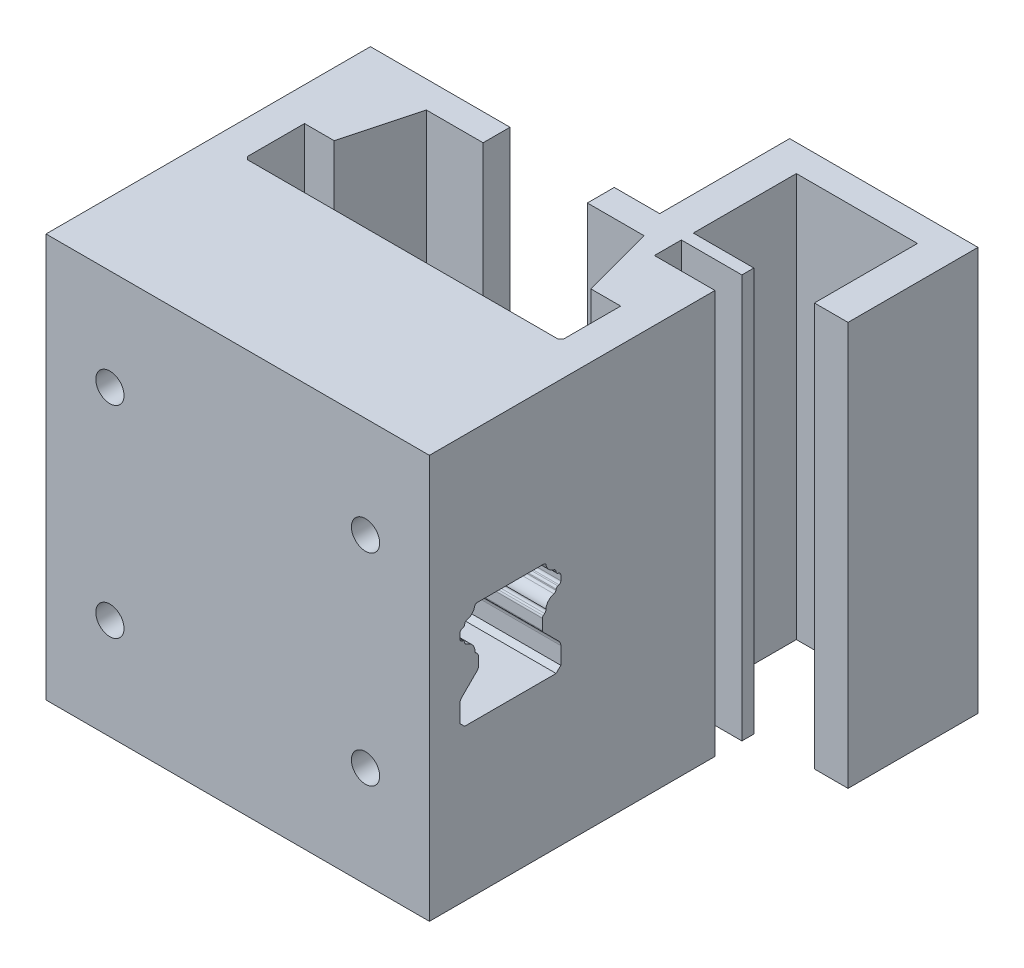
SolidWorks part; units mm, degrees
ref_plane "Front Plane" through (0, 0, 0) normal (0, 0, 1) x (1, 0, 0)
ref_plane "Top Plane" through (0, 0, 0) normal (0, 1, 0) x (1, 0, 0)
ref_plane "Right Plane" through (0, 0, 0) normal (1, 0, 0) x (0, 0, -1)
sketch "Sketch1" plane through (0, 0, 0) normal (0, 1, 0) x (1, 0, 0)
  line L0 (23.07, -9.85) -> (-23.07, -9.85)
  line L1 (-23.5, -9.42) -> (-23.07, -9.85)
  line L2 (-23.5, -9.42) -> (-23.5, -0.95)
  line L7 (-19.0939, -0.95) -> (-23.5, -0.95)
  line L8 (-19.0939, -0.95) -> (-19, -0.5997)
  line L9 (-16.2, 9.85) -> (-19, -0.5997)
  line L10 (16.2, 9.85) -> (-16.2, 9.85)
  line L11 (23.07, -9.85) -> (23.5, -9.42)
  line L12 (23.5, -2.9) -> (23.5, -9.42)
  line L13 (23.5, -2.9) -> (23.5, -0.95)
  line L15 (19.0939, -0.95) -> (23.5, -0.95)
  line L16 (19.0939, -0.95) -> (19, -0.5997)
  line L17 (16.2, 9.85) -> (19, -0.5997)
  line L18 (-28.5, -14.85) -> (28.5, -14.85)
  line L19 (-28.5, -14.85) -> (-28.5, 13.85)
  line L20 (-28.5, 13.85) -> (28.5, 13.85)
  line L21 (28.5, -14.85) -> (28.5, 13.85)
  dimension "D1" = 5
  dimension "D2" = 5
  dimension "D3" = 5
  dimension "D4" = 4
extrude "Boss-Extrude1" add sketch "Sketch1" along normal blind 60
sketch "Sketch2" plane through (0, 0, 0) normal (0, -1, 0) x (1, 0, 0)
  line L0 (0, -25.3794) -> (0, 27.4746) construction
  line L1 (28.5, -8.0706) -> (19.5, -8.0706)
  line L2 (28.5, -8.0706) -> (28.5, -12.0706)
  line L3 (28.5, -12.0706) -> (19.5, -12.0706)
  line L4 (19.5, -8.0706) -> (19.5, -12.0706)
  line L5 (-19.5, -8.0706) -> (-19.5, -12.0706)
  line L6 (-28.5, -12.0706) -> (-19.5, -12.0706)
  line L7 (-28.5, -8.0706) -> (-28.5, -12.0706)
  line L8 (-28.5, -8.0706) -> (-19.5, -8.0706)
  dimension "D1" = 9
  dimension "D2" = 4
extrude "Cut-Extrude1" cut sketch "Sketch2" against normal through all
sketch "Sketch5" plane through (0, 0, 0) normal (1, 0, 0) x (0, 0, -1)
  line L0 (-14.85, 23.2) -> (-14.85, 34.0815)
  line L1 (-15.55, 22.5) -> (-14.85, 23.2)
  line L2 (-29.15, 22.5) -> (-15.55, 22.5)
  line L3 (-29.85, 23.2) -> (-29.15, 22.5)
  line L4 (-29.85, 25.7434) -> (-29.85, 23.2)
  line L5 (-27.2372, 28.7704) -> (-29.5571, 26.4505)
  line L6 (-27.12, 30.6153) -> (-27.12, 29.0533)
  line L7 (-27.4316, 31.0926) -> (-27.2372, 30.8982)
  line L8 (-29.1562, 33.3541) -> (-29.1243, 33.2128)
  line L9 (-29.5857, 33.7052) -> (-29.4106, 33.6421)
  line L10 (-29.85, 34.8375) -> (-29.85, 34.0815)
  line L11 (-29.4277, 35.2633) -> (-29.5687, 35.2195)
  line L12 (-29.125, 35.7021) -> (-29.1553, 35.5612)
  line L13 (-27.399, 37.5) -> (-27.4361, 37.4629)
  line L14 (-17.301, 37.5) -> (-27.399, 37.5)
  line L15 (-17.2639, 37.4629) -> (-17.301, 37.5)
  line L16 (-15.5447, 35.5612) -> (-15.575, 35.7021)
  line L17 (-15.1313, 35.2195) -> (-15.2723, 35.2633)
  line L18 (-14.85, 34.0815) -> (-14.85, 60)
  line L19 (-15.2894, 33.6421) -> (-15.1143, 33.7052)
  line L20 (-15.5757, 33.2128) -> (-15.5438, 33.3541)
  line L21 (-17.4628, 30.8982) -> (-17.2684, 31.0926)
  line L22 (-17.58, 29.0533) -> (-17.58, 30.6153)
  line L23 (-15.1429, 26.4505) -> (-17.4628, 28.7704)
  line L24 (-14.85, 60) -> (-34.3805, 60)
  line L25 (-14.85, 30) -> (-29.85, 30) construction
  line L26 (-34.3805, 60) -> (-34.3805, 0)
  line L27 (-14.85, 34.0815) -> (-14.85, 30) construction
  line L28 (-34.3805, 0) -> (-14.85, 0)
  line L29 (-14.85, 0) -> (-14.85, 23.2)
  arc A0 (-14.85, 25.7434) -> (-15.1429, 26.4505) centre (-15.85, 25.7434) ccw
  arc A1 (-29.5571, 26.4505) -> (-29.85, 25.7434) centre (-28.85, 25.7434) ccw
  arc A2 (-27.2372, 28.7704) -> (-27.12, 29.0533) centre (-27.52, 29.0533) ccw
  arc A3 (-27.12, 30.6153) -> (-27.2372, 30.8982) centre (-27.52, 30.6153) ccw
  arc A4 (-27.6206, 31.5718) -> (-27.4316, 31.0926) centre (-27.2414, 31.4445) ccw
  arc A5 (-27.6206, 31.5718) -> (-28.8285, 32.9123) centre (-29.2062, 31.3576) ccw
  arc A6 (-29.1243, 33.2128) -> (-28.8285, 32.9123) centre (-28.7341, 33.301) ccw
  arc A7 (-29.1562, 33.3541) -> (-29.4106, 33.6421) centre (-29.5464, 33.2658) ccw
  arc A8 (-29.85, 34.0815) -> (-29.5857, 33.7052) centre (-29.45, 34.0815) ccw
  arc A9 (-29.5687, 35.2195) -> (-29.85, 34.8375) centre (-29.45, 34.8375) ccw
  arc A10 (-29.4277, 35.2633) -> (-29.1553, 35.5612) centre (-29.5464, 35.6453) ccw
  arc A11 (-28.8284, 36.0067) -> (-29.125, 35.7021) centre (-28.734, 35.618) ccw
  arc A12 (-28.8284, 36.0067) -> (-27.624, 37.3234) centre (-29.2062, 37.5614) ccw
  arc A13 (-27.4361, 37.4629) -> (-27.624, 37.3234) centre (-27.3021, 37.086) ccw
  arc A14 (-17.076, 37.3234) -> (-17.2639, 37.4629) centre (-17.3979, 37.086) ccw
  arc A15 (-17.076, 37.3234) -> (-15.8716, 36.0067) centre (-15.4938, 37.5614) ccw
  arc A16 (-15.575, 35.7021) -> (-15.8716, 36.0067) centre (-15.966, 35.618) ccw
  arc A17 (-15.5447, 35.5612) -> (-15.2723, 35.2633) centre (-15.1536, 35.6453) ccw
  arc A18 (-14.85, 34.8375) -> (-15.1313, 35.2195) centre (-15.25, 34.8375) ccw
  arc A19 (-15.1143, 33.7052) -> (-14.85, 34.0815) centre (-15.25, 34.0815) ccw
  arc A20 (-15.2894, 33.6421) -> (-15.5438, 33.3541) centre (-15.1536, 33.2658) ccw
  arc A21 (-15.8715, 32.9123) -> (-15.5757, 33.2128) centre (-15.9659, 33.301) ccw
  arc A22 (-15.8715, 32.9123) -> (-17.0794, 31.5718) centre (-15.4938, 31.3576) ccw
  arc A23 (-17.2684, 31.0926) -> (-17.0794, 31.5718) centre (-17.4586, 31.4445) ccw
  arc A24 (-17.4628, 30.8982) -> (-17.58, 30.6153) centre (-17.18, 30.6153) ccw
  arc A25 (-17.58, 29.0533) -> (-17.4628, 28.7704) centre (-17.18, 29.0533) ccw
  dimension "D1" = 15
  dimension "D2" = 7.5
extrude "Boss-Extrude2" add sketch "Sketch5" along normal mid plane 57 contours A18 L18 L24 L26 L28 L29 L1 L2 L3 L4 A1 L5 A2 L6 A3 L7 A4 A5 A6 L8 A7 L9 A8 L10 A9 L11 A10 L12 A11 A12 A13 L13 L14 L15 A14 A15 A16 L16 A17 L17 | L22 A25 L23 A0 L0 A19 L19 A20 L20 A21 A22 A23 L21 A24
sketch "Sketch6" plane through (0, 60, 0) normal (0, 1, 0) x (1, 0, 0)
  line L0 (0, 26.3935) -> (0, -49.3571) construction
  line L1 (28.5, 13.85) -> (-28.5, 13.85) construction
  line L2 (-7.75, 19.7454) -> (7.75, 19.7454)
  line L3 (-7.75, 19.7454) -> (-7.75, 4.3549)
  line L4 (-7.75, 4.3549) -> (7.75, 4.3549)
  line L5 (7.75, 19.7454) -> (7.75, 4.3549)
  dimension "D1" = 5.8954
  dimension "D2" = 15.5
extrude "Cut-Extrude2" cut sketch "Sketch6" against normal blind 80
sketch "Sketch9" plane through (0, 60, 0) normal (0, 1, 0) x (1, 0, 0)
  line L0 (-19.5, 13.85) -> (-19.5, 29.1706)
  line L1 (-19.5, 29.1706) -> (-37.5, 29.1706)
  line L3 (-28.5, 23.1706) -> (-28.5, 8.0706) construction
  line L4 (-19.5, 12.0706) -> (-19.5, 8.0706) construction
  line L5 (-7.75, 13.85) -> (-28.5, 13.85) construction
  line L6 (-14.5, 13.85) -> (-14.5, 33.1706)
  line L10 (-14.5, 13.85) -> (-19.5, 13.85)
  line L11 (-19.25, 24.1706) -> (-28.75, 24.1706) construction
  line L12 (0, -34.3805) -> (0, 38.6423) construction
  line L13 (28.5, -34.3805) -> (-28.5, -34.3805) construction
  line L14 (-42.5, 13.85) -> (-37.5, 13.85)
  line L16 (-42.5, 33.1706) -> (-14.5, 33.1706)
  line L17 (-42.5, 13.85) -> (-42.5, 33.1706)
  line L18 (-37.5, 13.85) -> (-37.5, 29.1706)
  line L19 (28.5, 23.1706) -> (28.5, 8.0706) construction
  line L20 (37.5, 13.85) -> (37.5, 29.1706)
  line L21 (42.5, 13.85) -> (42.5, 33.1706)
  line L24 (42.5, 13.85) -> (37.5, 13.85)
  line L25 (14.5, 13.85) -> (19.5, 13.85)
  line L28 (14.5, 33.1706) -> (42.5, 33.1706)
  line L29 (14.5, 13.85) -> (14.5, 33.1706)
  line L31 (19.5, 29.1706) -> (37.5, 29.1706)
  line L32 (19.5, 13.85) -> (19.5, 29.1706)
  dimension "D1" = 5
  dimension "D5" = 5
extrude "Boss-Extrude5" add sketch "Sketch9" against normal up to surface (60 mm away) up to face at (0, 0, -2.4717)
sketch "Sketch10" plane through (0, 0, 34.3805) normal (0, 0, 1) x (1, 0, 0)
  line L0 (-28.5, 30) -> (28.5, 30) construction
  line L1 (-28.5, 60) -> (-28.5, 0) construction
  line L2 (28.5, 60) -> (28.5, 0) construction
  line L4 (-19, 15) -> (19, 15) construction
  line L5 (-19, 15) -> (-19, 45) construction
  line L6 (-19, 45) -> (19, 45) construction
  line L7 (19, 15) -> (19, 45) construction
  line L8 (-19, 15) -> (19, 45) construction
  line L9 (-19, 45) -> (19, 15) construction
  circle A0 centre (-19, 45) radius 2.1
  circle A1 centre (19, 45) radius 2.1
  circle A2 centre (-19, 15) radius 2.1
  circle A3 centre (19, 15) radius 2.1
  point P6 (0, 30)
  dimension "D3" = 4.2
  dimension "D1" = 30
  dimension "D2" = 38
extrude "Cut-Extrude3" cut sketch "Sketch10" against normal up to surface (24.5305 mm away) up to face at (0, 30, 9.85)
sketch "Sketch11" plane through (0, 0, 0) normal (0, -1, 0) x (1, 0, 0)
  line L1 (-47.9136, -33.9347) -> (-7.75, -33.9347)
  line L2 (-47.9136, -33.9347) -> (-47.9136, -13.85)
  line L3 (-47.9136, -13.85) -> (-7.75, -13.85)
  line L4 (-7.75, -33.9347) -> (-7.75, -13.85)
  line L5 (-47.9136, -33.9347) -> (-7.75, -13.85) construction
  line L6 (-47.9136, -13.85) -> (-7.75, -33.9347) construction
  point P0 (-27.8318, -23.8923)
extrude "Cut-Extrude4" cut sketch "Sketch11" against normal through all
sketch "Sketch12" plane through (0, 0, 0) normal (0, -1, 0) x (-1, 0, 0)
  line L1 (28.5, 8.0706) -> (19.5, 8.0706)
  line L2 (28.5, 8.0706) -> (28.5, 12.0706)
  line L3 (28.5, 12.0706) -> (19.5, 12.0706)
  line L4 (19.5, 8.0706) -> (19.5, 12.0706)
extrude "Boss-Extrude6" add sketch "Sketch12" against normal through all
